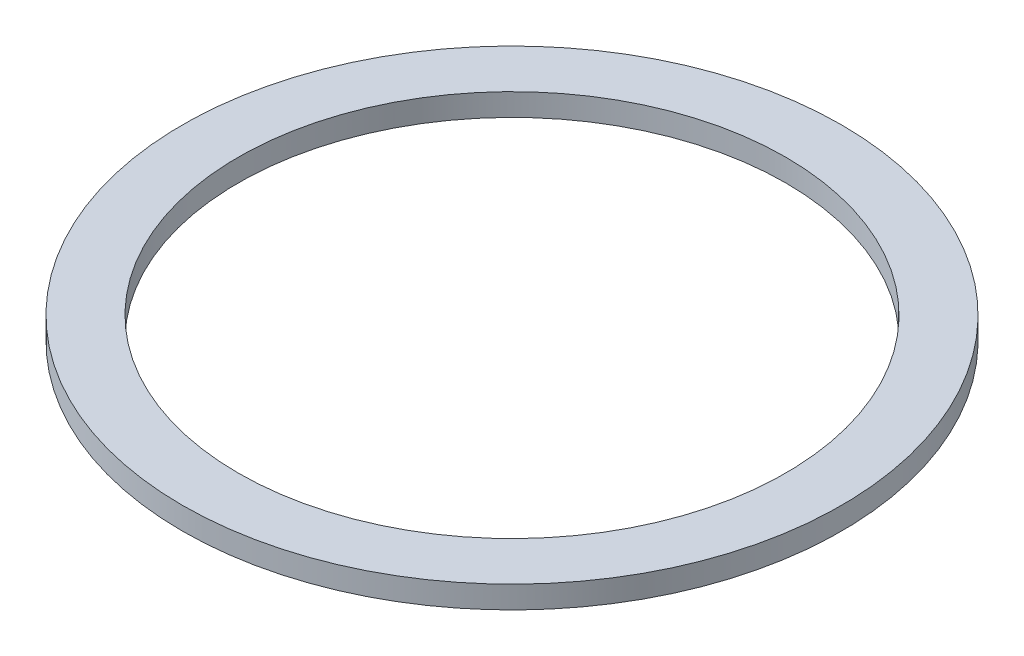
SolidWorks part; units mm, degrees
ref_plane "Спереди" through (0, 0, 0) normal (0, 0, 1) x (1, 0, 0)
ref_plane "Сверху" through (0, 0, 0) normal (0, 1, 0) x (1, 0, 0)
ref_plane "Справа" through (0, 0, 0) normal (1, 0, 0) x (0, 0, -1)
sketch "Эскиз1" plane through (0, 0, 0) normal (0, 1, 0) x (1, 0, 0)
  circle A0 centre (0, 0) radius 24.5
  circle A1 centre (0, 0) radius 29.5
  dimension "D1" = 49
  dimension "D2" = 59
extrude "Бобышка-Вытянуть1" add sketch "Эскиз1" along normal blind 2
